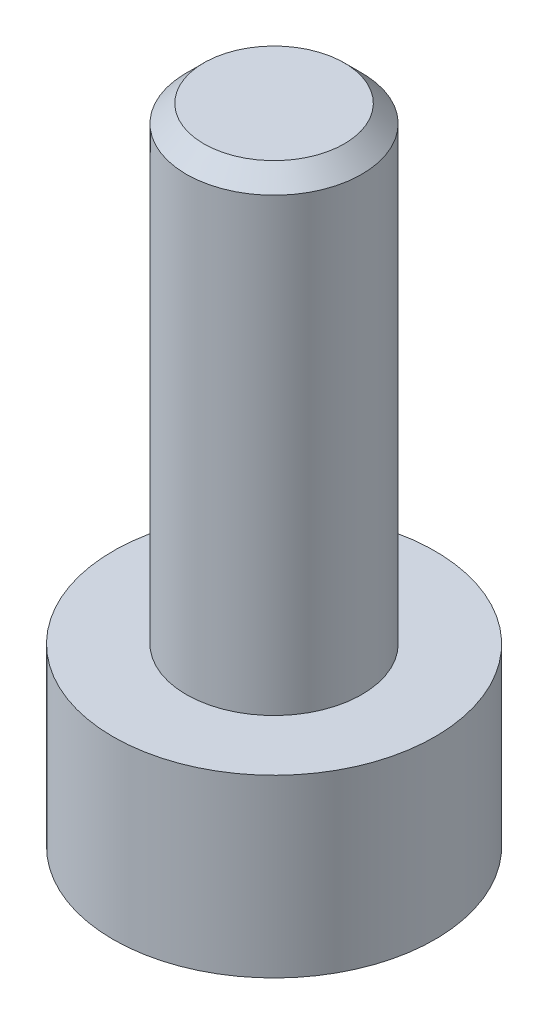
SolidWorks part; units mm, degrees
ref_plane "前视基准面" through (0, 0, 0) normal (0, 0, 1) x (1, 0, 0)
ref_plane "上视基准面" through (0, 0, 0) normal (0, 1, 0) x (1, 0, 0)
ref_plane "右视基准面" through (0, 0, 0) normal (1, 0, 0) x (0, 0, -1)
sketch "草图1" plane through (0, 0, 0) normal (0, 1, 0) x (1, 0, 0)
  circle A0 centre (0, 0) radius 2.75
  dimension "D1" = 5.5
extrude "凸台-拉伸1" add sketch "草图1" along normal blind 3
sketch "草图2" plane through (0, 3, 0) normal (0, 1, 0) x (1, 0, 0)
  circle A0 centre (0, 0) radius 1.5
  dimension "D1" = 3
sketch "草图3" plane through (0, 0, 0) normal (0, -1, 0) x (1, 0, 0)
  line L1 (0, 1.25) -> (-1.0825, 0.625)
  line L2 (-1.0825, 0.625) -> (-1.0825, -0.625)
  line L3 (-1.0825, -0.625) -> (0, -1.25)
  line L4 (0, -1.25) -> (1.0825, -0.625)
  line L5 (1.0825, -0.625) -> (1.0825, 0.625)
  line L6 (1.0825, 0.625) -> (0, 1.25)
  circle A0 centre (0, 0) radius 1.0825 construction
  dimension "D1" = 2.5
extrude "切除-拉伸1" cut sketch "草图3" against normal blind 1.5
extrude "凸台-拉伸2" add sketch "草图2" along normal blind 8
cosmetic thread "装饰螺纹线1" parameters "D2"=2
chamfer "倒角1" distance 0.3 angle 45 1 edges at (0, 11, 1.5)
scale "缩放比例1" scale about centroid uniform scaling yes scale factor 2
